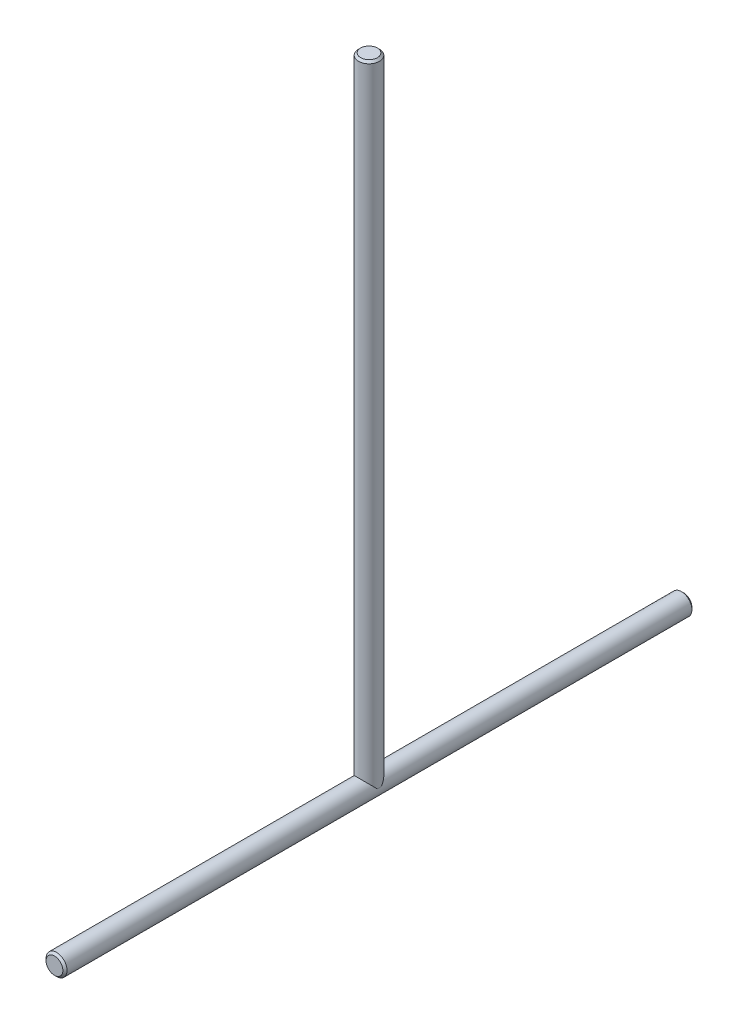
SolidWorks part; units mm, degrees
ref_plane "Front" through (0, 0, 0) normal (0, 0, 1) x (1, 0, 0)
ref_plane "Top" through (0, 0, 0) normal (0, 1, 0) x (1, 0, 0)
ref_plane "Right" through (0, 0, 0) normal (1, 0, 0) x (0, 0, -1)
sketch "Sketch1" plane through (0, 0, 0) normal (0, 0, 1) x (1, 0, 0)
  line L0 (0, 0) -> (0, 302)
  line L1 (0, 302) -> (4, 302)
  line L2 (5, 301) -> (5, 1)
  line L3 (4, 0) -> (0, 0)
  line L4 (4, 302) -> (5, 301)
  line L5 (5, 1) -> (4, 0)
  point P4 (5, 302)
  point P5 (5, 0)
  dimension "D1" = 5
  dimension "D2" = 300
revolve "Revolve1" add sketch "Sketch1" angle 360 about L0
sketch "Sketch2" plane through (0, 0, 0) normal (0, 0, 1) x (1, 0, 0)
  circle A0 centre (0, 0) radius 5
  dimension "D1" = 10
extrude "Boss-Extrude1" add sketch "Sketch2" along normal mid plane 300
chamfer "Chamfer1" distance 1 angle 45 2 edges at (5, 0, 150) (5, 0, -150)
